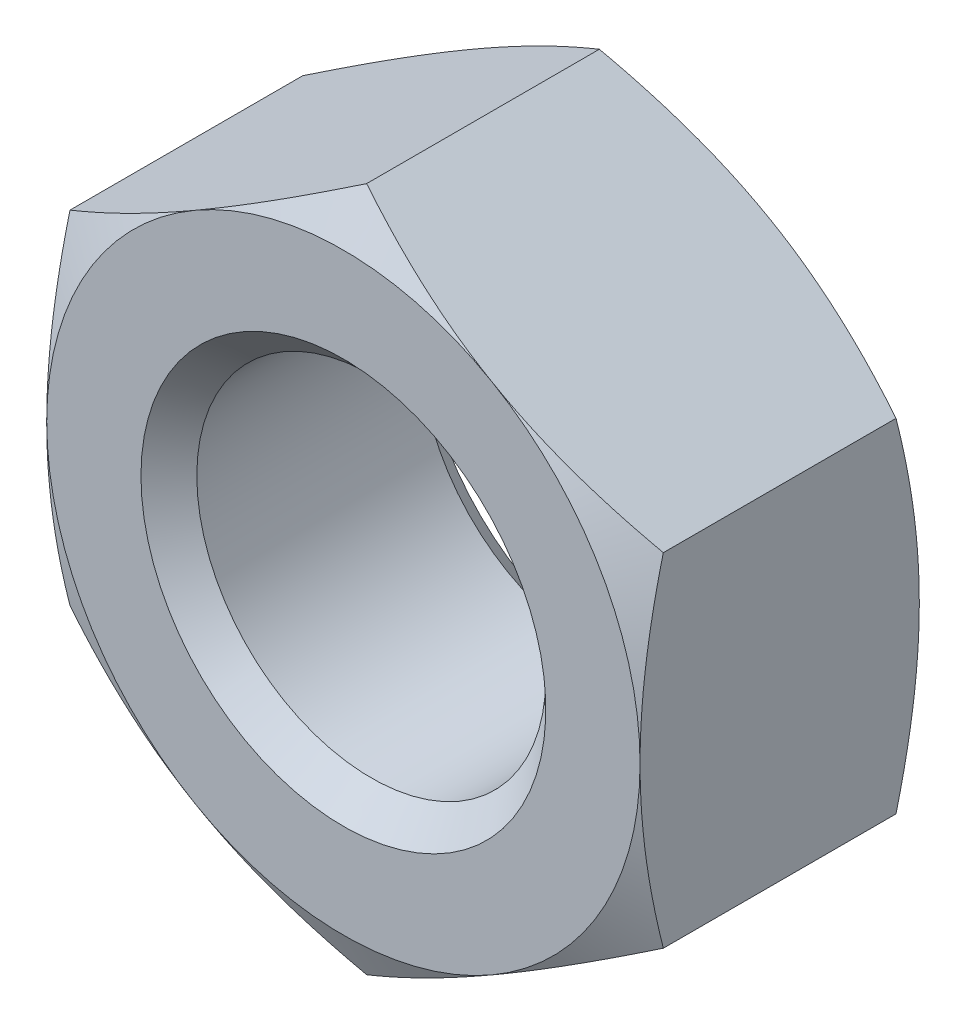
SolidWorks part; units mm, degrees
material "Plain Carbon Steel"
ref_plane "Front Plane" through (0, 0, 0) normal (0, 0, 1) x (1, 0, 0)
ref_plane "Top Plane" through (0, 0, 0) normal (0, 1, 0) x (1, 0, 0)
ref_plane "Right Plane" through (0, 0, 0) normal (1, 0, 0) x (0, 0, -1)
sketch "Sketch1" plane through (0, 0, 0) normal (0, 0, 1) x (1, 0, 0)
  line L1 (0, -9.815) -> (8.5, -4.9075)
  line L2 (8.5, -4.9075) -> (8.5, 4.9075)
  line L3 (8.5, 4.9075) -> (0, 9.815)
  line L4 (0, 9.815) -> (-8.5, 4.9075)
  line L5 (-8.5, 4.9075) -> (-8.5, -4.9075)
  line L6 (-8.5, -4.9075) -> (0, -9.815)
  circle A0 centre (0, 0) radius 8.5 construction
  circle A1 centre (0, 0) radius 5
  dimension "D2" = 10
  dimension "D1" = 17
extrude "Boss-Extrude1" add sketch "Sketch1" along normal blind 8
sketch "Sketch2" plane through (0, 0, 0) normal (1, 0, 0) x (0, 0, -1)
  line L0 (-8, 9.815) -> (-8, 8.5)
  line L1 (-8, 4.9075) -> (-8, 9.815) construction
  line L2 (-8, 8.5) -> (-7.3333, 9.815)
  line L3 (-8, 9.815) -> (0, 9.815) construction
  line L4 (-7.3333, 9.815) -> (-8, 9.815)
  line L5 (-0.6667, 9.815) -> (0, 9.815)
  line L6 (0, 9.815) -> (0, 8.5)
  line L7 (0, 4.9075) -> (0, 9.815) construction
  line L8 (0, 8.5) -> (-0.6667, 9.815)
  line L9 (-7.3333, 9.815) -> (-6.6667, 9.815) construction
  line L10 (-6.6667, 9.815) -> (-6, 9.815) construction
  line L11 (-6, 9.815) -> (-5.3333, 9.815) construction
  line L12 (-5.3333, 9.815) -> (-4.6667, 9.815) construction
  line L13 (-4.6667, 9.815) -> (-4, 9.815) construction
  line L14 (-4, 9.815) -> (-3.3333, 9.815) construction
  line L15 (-3.3333, 9.815) -> (-2.6667, 9.815) construction
  line L16 (-2.6667, 9.815) -> (-2, 9.815) construction
  line L17 (-2, 9.815) -> (-1.3333, 9.815) construction
  line L18 (0, 0) -> (-8, 0) construction
  line L19 (-8, -4.9075) -> (-8, 4.9075) construction
  line L20 (-8, 5) -> (-7.2, 5)
  line L21 (-7.2, 5) -> (-8, 5.8)
  line L22 (-8, 5.8) -> (-8, 5)
  line L23 (0, 5) -> (-0.8, 5)
  line L24 (0, -4.9075) -> (0, 4.9075) construction
  line L25 (-0.8, 5) -> (0, 5.8)
  line L26 (0, 5.8) -> (0, 5)
  line L29 (-7.2, 5) -> (-6.4, 5) construction
  line L30 (-6.4, 5) -> (-5.6, 5) construction
  line L31 (-5.6, 5) -> (-4.8, 5) construction
  line L32 (-4.8, 5) -> (-4, 5) construction
  line L33 (-4, 5) -> (-3.2, 5) construction
  line L34 (-3.2, 5) -> (-2.4, 5) construction
  line L35 (-2.4, 5) -> (-1.6, 5) construction
  line L36 (-1.6, 5) -> (-0.8, 5) construction
  line L37 (-1.3333, 9.815) -> (-0.6667, 9.815) construction
  dimension "D1" = 17
revolve "Cut-Revolve1" cut sketch "Sketch2" angle 360 about L18
